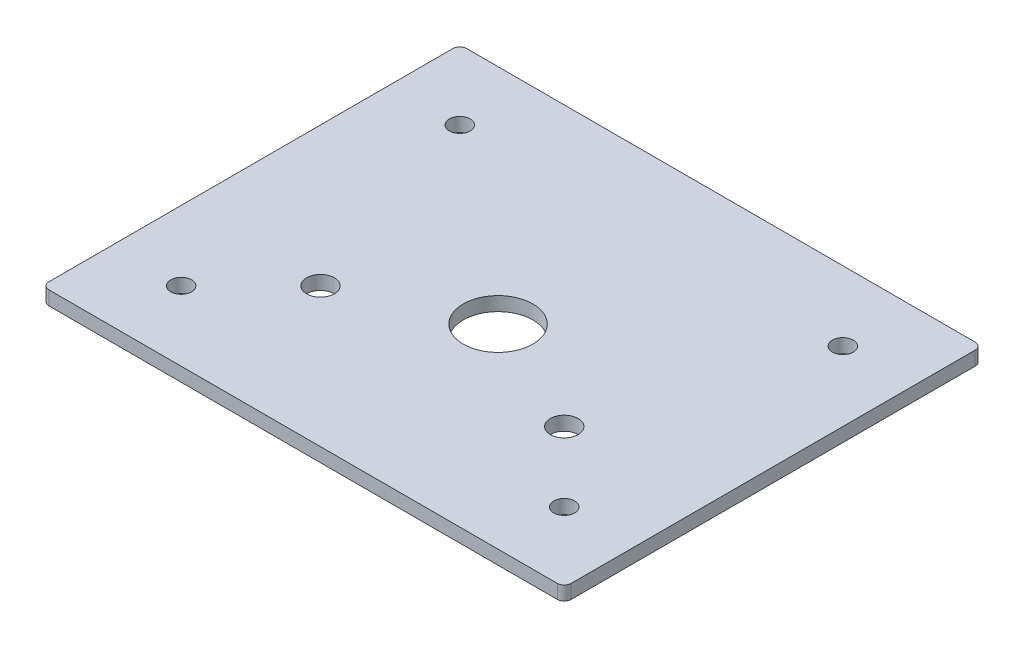
SolidWorks part; units mm, degrees
ref_plane "Front Plane" through (0, 0, 0) normal (0, 0, 1) x (1, 0, 0)
ref_plane "Top Plane" through (0, 0, 0) normal (0, 1, 0) x (1, 0, 0)
ref_plane "Right Plane" through (0, 0, 0) normal (1, 0, 0) x (0, 0, -1)
sketch "Sketch2" plane through (0, 0, 0) normal (0, 1, 0) x (1, 0, 0)
  line L1 (0, 0) -> (75, 0)
  line L2 (0, 0) -> (0, 60)
  line L3 (0, 60) -> (75, 60)
  line L4 (75, 0) -> (75, 60)
  dimension "D1" = 75
  dimension "D2" = 60
extrude "Boss-Extrude1" add sketch "Sketch2" along normal blind 2
sketch "Sketch4" plane through (0, 2, 0) normal (0, 1, 0) x (1, 0, 0)
  line L0 (0, 0) -> (75, 0) construction
  line L2 (0, 60) -> (0, 0) construction
  line L3 (75, 0) -> (75, 60) construction
  line L4 (0, 60) -> (0, 30)
  line L6 (0, 0) -> (0, 10)
  line L7 (0, 10) -> (10, 10)
  line L9 (75, 60) -> (0, 60) construction
  line L11 (75, 0) -> (75, 10)
  line L12 (75, 10) -> (65, 10)
  circle A3 centre (10, 10) radius 1.5
  circle A5 centre (65, 10) radius 1.5
  circle A7 centre (20, 20) radius 2
  circle A8 centre (55, 20) radius 2
  circle A9 centre (10, 50) radius 1.5
  circle A10 centre (65, 50) radius 1.5
  dimension "D5" = 10
  dimension "D6" = 20
  dimension "D7" = 20
  dimension "D10" = 20
  dimension "D12" = 10
  dimension "D14" = 10
  dimension "D15" = 10
  dimension "D2" = 3
  dimension "D3" = 10
  dimension "D4" = 10
  dimension "D11" = 20
  dimension "D8" = 10
  dimension "D9" = 10
  dimension "D13" = 10
extrude "Cut-Extrude2" cut sketch "Sketch4" against normal blind 2
sketch "Sketch5" plane through (0, 2, 0) normal (0, 1, 0) x (1, 0, 0)
  line L0 (37.5, 60) -> (37.5, 28)
  line L2 (75, 60) -> (0, 60) construction
  circle A3 centre (37.5, 28) radius 5
extrude "Cut-Extrude3" cut sketch "Sketch5" against normal blind 40
fillet "Fillet1" radius 1 4 edges at (75, 1, -60) (75, 1, 0) (0, 1, 0) (0, 1, -60)
